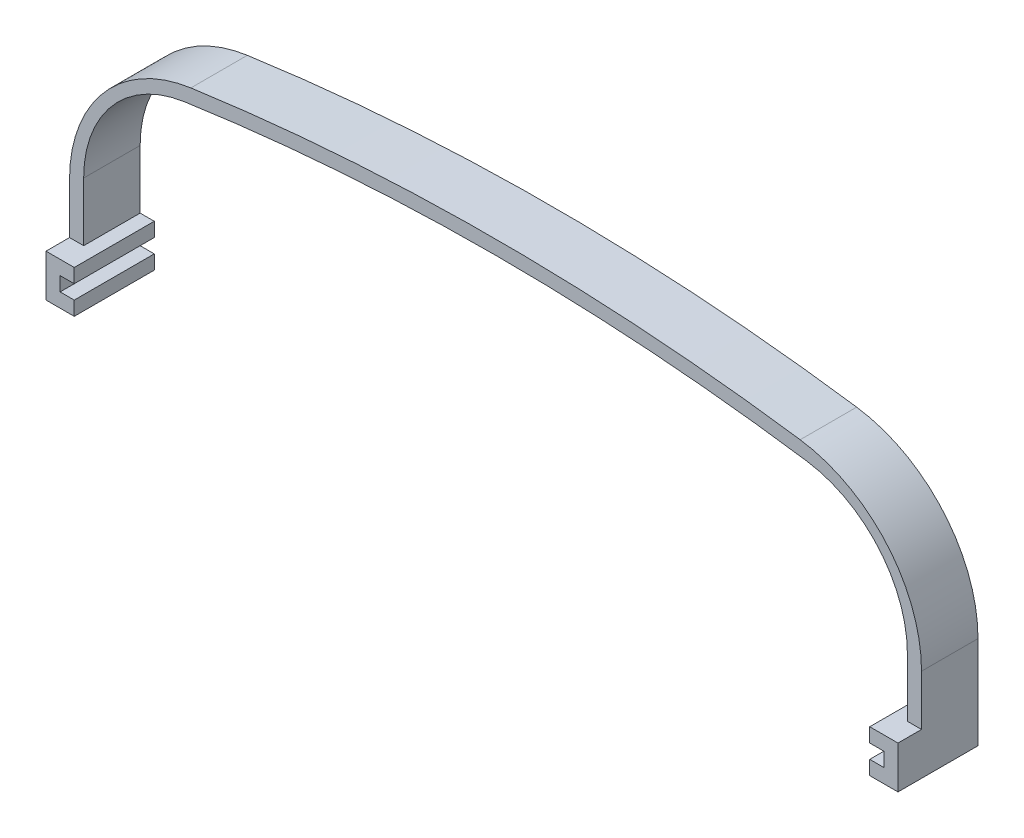
SolidWorks part; units mm, degrees
ref_plane "Front" through (0, 0, 0) normal (0, 0, 1) x (1, 0, 0)
ref_plane "Top" through (0, 0, 0) normal (0, 1, 0) x (1, 0, 0)
ref_plane "Right" through (0, 0, 0) normal (1, 0, 0) x (0, 0, -1)
sketch "Sketch1" plane through (0, 0, 0) normal (0, 0, 1) x (1, 0, 0)
  line L0 (84.5, 0) -> (87.5, 0)
  line L1 (87.5, 0) -> (87.5, 3)
  line L2 (87.5, 3) -> (84.5, 3)
  line L3 (84.5, 3) -> (84.5, 6)
  line L4 (84.5, 6) -> (87.5, 6)
  line L5 (87.5, 6) -> (87.5, 39.536)
  line L6 (0, 0) -> (0, 48) construction
  line L7 (84.5, 0) -> (84.5, -3)
  line L8 (84.5, -3) -> (90.5, -3)
  line L9 (90.5, -3) -> (90.5, 42)
  line L10 (0, 48) -> (0, 51)
  line L11 (87.5, 3) -> (90.5, 3) construction
  line L12 (0, 48) -> (-53.0529, 48) construction
  arc A0 (87.5, 39.536) -> (0, 48) centre (0, -408.5139) ccw
  arc A2 (0, 51) -> (90.5, 42) centre (0, -408.5139) cw
  point P9 (92.5, 48.0957)
  point P17 (92.5, 44.0729)
  point P18 (87.5, 3)
  dimension "D1" = 45
  dimension "D2" = 87.5
  dimension "D3" = 3
  dimension "D4" = 3
  dimension "D5" = 3
  dimension "D6" = 45
extrude "Boss-Extrude1" add sketch "Sketch1" along normal blind 12
sketch "Sketch2" plane through (0, 0, 12) normal (0, 0, 1) x (1, 0, 0)
  line L0 (90.5, -3) -> (84.5, -3)
  line L1 (84.5, -3) -> (84.5, 0)
  line L2 (84.5, 0) -> (87.5, 0)
  line L3 (87.5, 0) -> (87.5, 3)
  line L4 (87.5, 3) -> (84.5, 3)
  line L5 (84.5, 3) -> (84.5, 6)
  line L6 (84.5, 6) -> (90.5, 6)
  line L7 (90.5, -3) -> (90.5, 42) construction
  line L8 (90.5, 6) -> (90.5, -3)
extrude "Boss-Extrude2" add sketch "Sketch2" along normal blind 5
mirror "Mirror1" about plane through (0, 0, 0) normal (1, 0, 0) of "Boss-Extrude2", "Boss-Extrude1"
fillet "Fillet1" radius 25 2 edges at (-87.5, 39.536, 6) (87.5, 39.536, 6)
fillet "Fillet2" radius 30 2 edges at (-90.5, 42, 6) (90.5, 42, 6)
